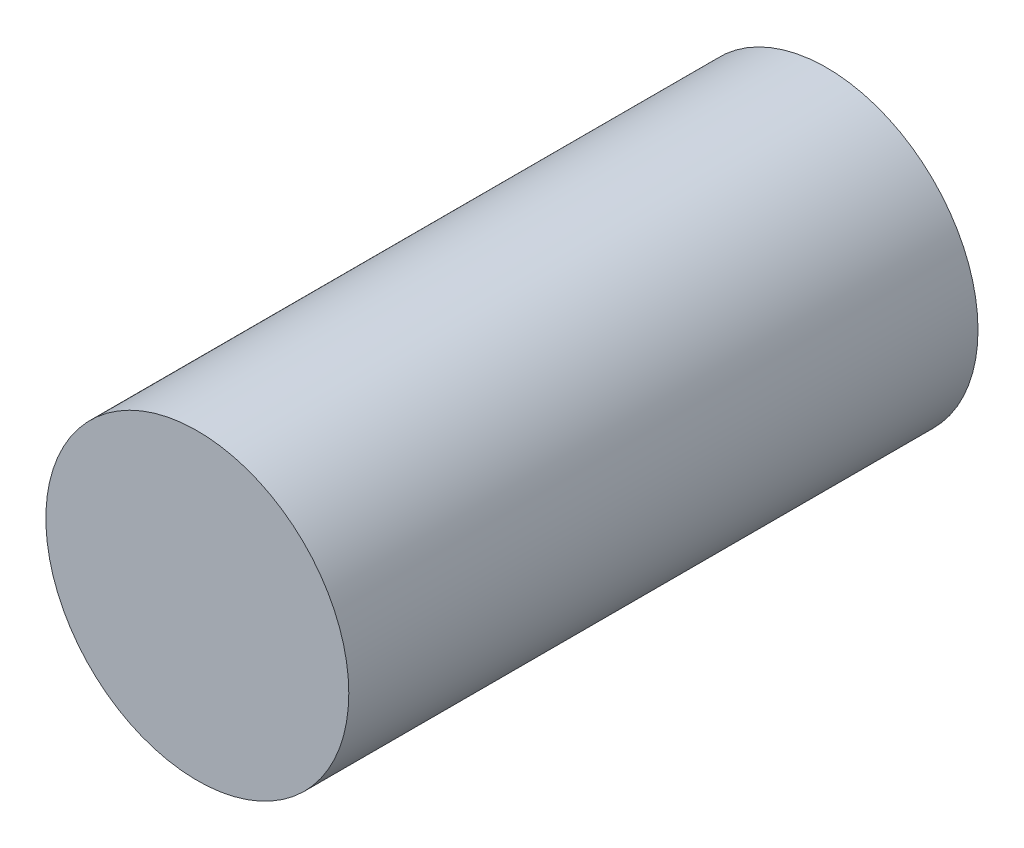
SolidWorks part; units mm, degrees
ref_plane "前视基准面" through (0, 0, 0) normal (0, 0, 1) x (1, 0, 0)
ref_plane "上视基准面" through (0, 0, 0) normal (0, 1, 0) x (1, 0, 0)
ref_plane "右视基准面" through (0, 0, 0) normal (1, 0, 0) x (0, 0, -1)
sketch "草图1" plane through (0, 0, 0) normal (0, 0, 1) x (1, 0, 0)
  circle A0 centre (0, 0) radius 6.5
  dimension "D1" = 13
extrude "凸台-拉伸1" add sketch "草图1" along normal blind 27
sketch "草图2" plane through (0, 0, 0) normal (0, 0, -1) x (-1, 0, 0)
  circle A0 centre (0, 0) radius 1.5
  dimension "D1" = 3
extrude "切除-拉伸1" cut sketch "草图2" against normal blind 8
